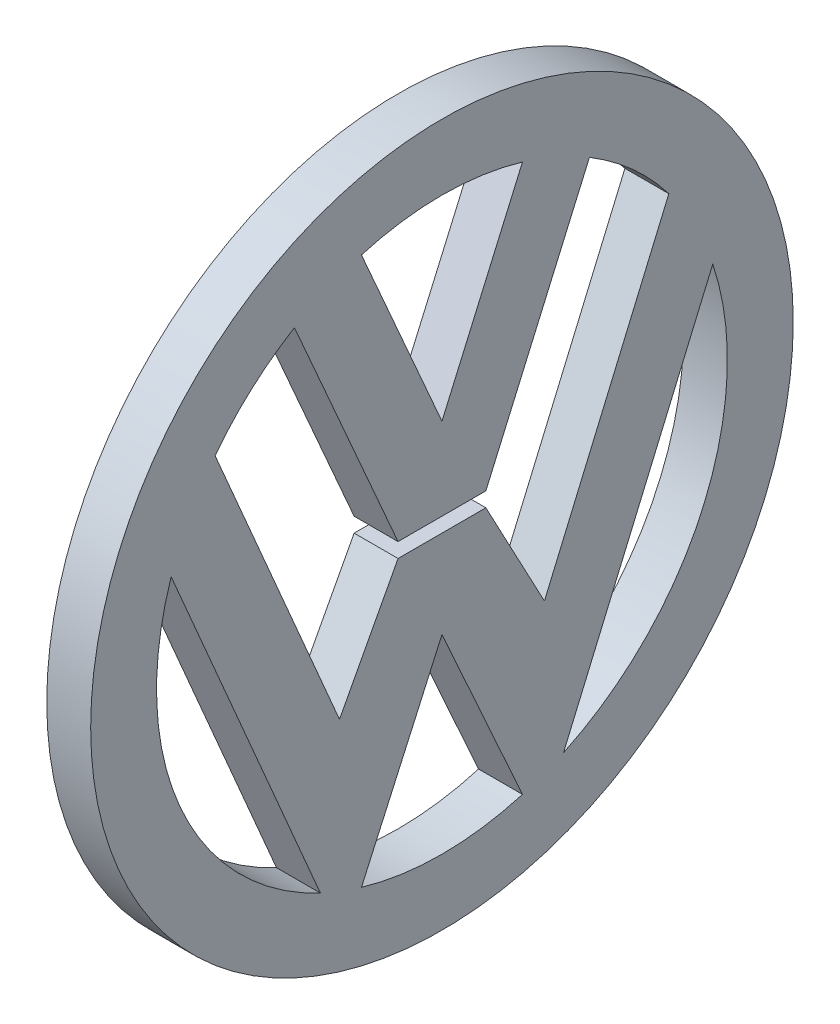
SolidWorks part; units mm, degrees
ref_plane "Спереди" through (0, 0, 0) normal (0, 0, 1) x (1, 0, 0)
ref_plane "Сверху" through (0, 0, 0) normal (0, 1, 0) x (1, 0, 0)
ref_plane "Справа" through (0, 0, 0) normal (1, 0, 0) x (0, 0, -1)
sketch "Эскиз5" plane through (0, 0, 0) normal (-1, 0, 0) x (0, 0, 1)
  line B0 (0, 0) -> (0, 19.5) construction
  line B1 (5.5, 18.7083) -> (0, 6.1217)
  line B2 (10.0766, 16.6947) -> (3, 0.5)
  line B3 (3, 0.5) -> (-3, 0.5)
  line B4 (0, 0) -> (-19.5, 0) construction
  line B5 (-5.5, 18.7083) -> (0, 6.1217)
  line B6 (-10.0766, 16.6947) -> (-3, 0.5)
  line B7 (-3, -0.5) -> (3, -0.5)
  line B8 (3, 0.5) -> (3, -0.5) construction
  line B9 (3, -0.5) -> (7, -8.0165)
  line B10 (7, -8.0165) -> (15.5, 11.8322)
  line B11 (0, -6.5) -> (5.5, -18.7083)
  line B12 (8.3046, -17.6432) -> (18.5, 6.1644)
  line B13 (0, -6.5) -> (-5.5, -18.7083)
  line B14 (-8.3046, -17.6432) -> (-18.5, 6.1644)
  line B15 (-7, -8.0165) -> (-15.5, 11.8322)
  line B16 (-3, -0.5) -> (-7, -8.0165)
  circle B17 centre (0, 0) radius 24
  arc B18 (5.5, 18.7083) -> (-5.5, 18.7083) centre (0, 0) ccw
  arc B19 (-10.0766, 16.6947) -> (-15.5, 11.8322) centre (0, 0) ccw
  arc B20 (15.5, 11.8322) -> (10.0766, 16.6947) centre (0, 0) ccw
  arc B21 (-18.5, 6.1644) -> (-8.3046, -17.6432) centre (0, 0) ccw
  arc B22 (8.3046, -17.6432) -> (18.5, 6.1644) centre (0, 0) ccw
  arc B23 (-5.5, -18.7083) -> (5.5, -18.7083) centre (0, 0) ccw
sketch_block_instance "Блок1-1"
sketch_block "Блок1" parameters "D1"=48, "D2"=39, "D3"=5, "D4"=6, "D5"=11, "D6"=0.5, "D7"=0.5, "D8"=3, "D9"=6, "D10"=31, "D11"=37
extrude "Бобышка-Вытянуть1" add sketch "Эскиз5" along normal blind 3
